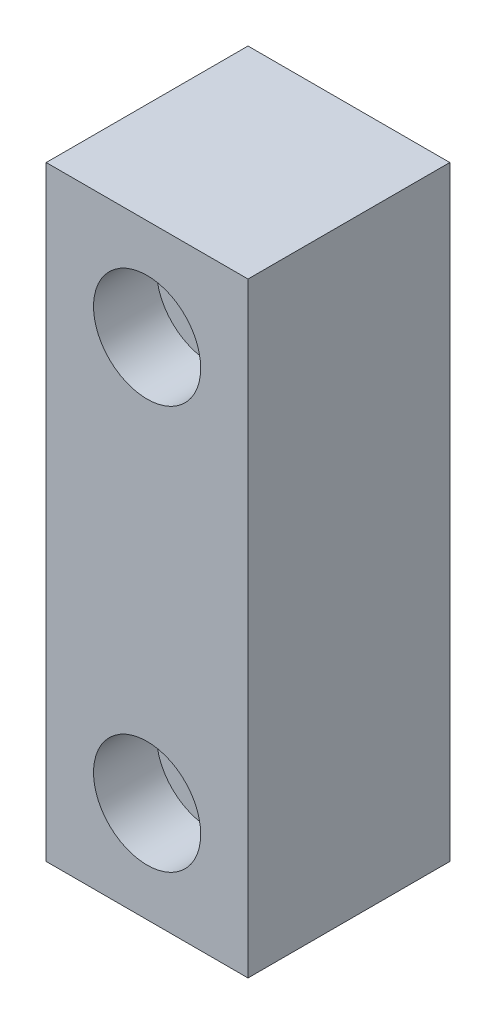
SolidWorks part; units mm, degrees
ref_plane "Front Plane" through (0, 0, 0) normal (1, 0, 0) x (0, 1, 0)
ref_plane "Top Plane" through (0, 0, 0) normal (0, 0, 1) x (0, 1, 0)
ref_plane "Right Plane" through (0, 0, 0) normal (0, 1, 0) x (-1, 0, 0)
sketch "Sketch1" plane through (0, 0, 0) normal (0, 0, 1) x (0, 1, 0)
  line L1 (-38.1, -12.7) -> (38.1, -12.7)
  line L2 (-38.1, -12.7) -> (-38.1, 12.7)
  line L3 (-38.1, 12.7) -> (38.1, 12.7)
  line L4 (38.1, -12.7) -> (38.1, 12.7)
  line L5 (-38.1, -12.7) -> (38.1, 12.7) construction
  line L6 (-38.1, 12.7) -> (38.1, -12.7) construction
  point P0 (0, 0)
  dimension "D1" = 38.1
  dimension "D2" = 12.7
extrude "Boss-Extrude1" add sketch "Sketch1" along normal mid plane 25.4
hole_wizard "CBORE for 5/16 Socket Head Cap Screw1" positions "Sketch3" profile "Sketch2" counterbore size "5/16" standard "ANSI Inch"
sketch "Sketch3" plane through (0, 0, 12.7) normal (0, 0, 1) x (1, 0, 0)
  line L0 (0, -25.4) -> (0, 25.4) construction
  line L1 (-12.7, 38.1) -> (-12.7, -38.1) construction
  line L2 (12.7, 38.1) -> (-12.7, 38.1) construction
  point P0 (0, -25.4)
  point P1 (0, 25.4)
  dimension "D1" = 12.7
  dimension "D2" = 12.7
  dimension "D3" = 12.7
  dimension "D4" = 63.5
sketch "Sketch2" plane through (0, -25.4, 12.7) normal (1, 0, 0) x (0, -1, 0)
  line L0 (0, 0) -> (0, 28.025)
  line L1 (0, 28.025) -> (4.3688, 25.4)
  line L2 (4.3688, 25.4) -> (4.3688, 7.9248)
  line L3 (4.3688, 7.9248) -> (6.7437, 7.9248)
  line L4 (6.7437, 7.9248) -> (6.7437, 0)
  line L5 (6.7437, 0) -> (0, 0)
  line L10 (0, 28.025) -> (-4.3688, 25.4) construction
  line L11 (0, -6.35) -> (0, 107.95) construction
  dimension "Hole Dia." = 8.7376
  dimension "Hole Depth" = 25.4
  dimension "C'Bore Dia." = 13.4874
  dimension "C'Bore Depth" = 7.9248
  dimension "Drill Angle" = 118
